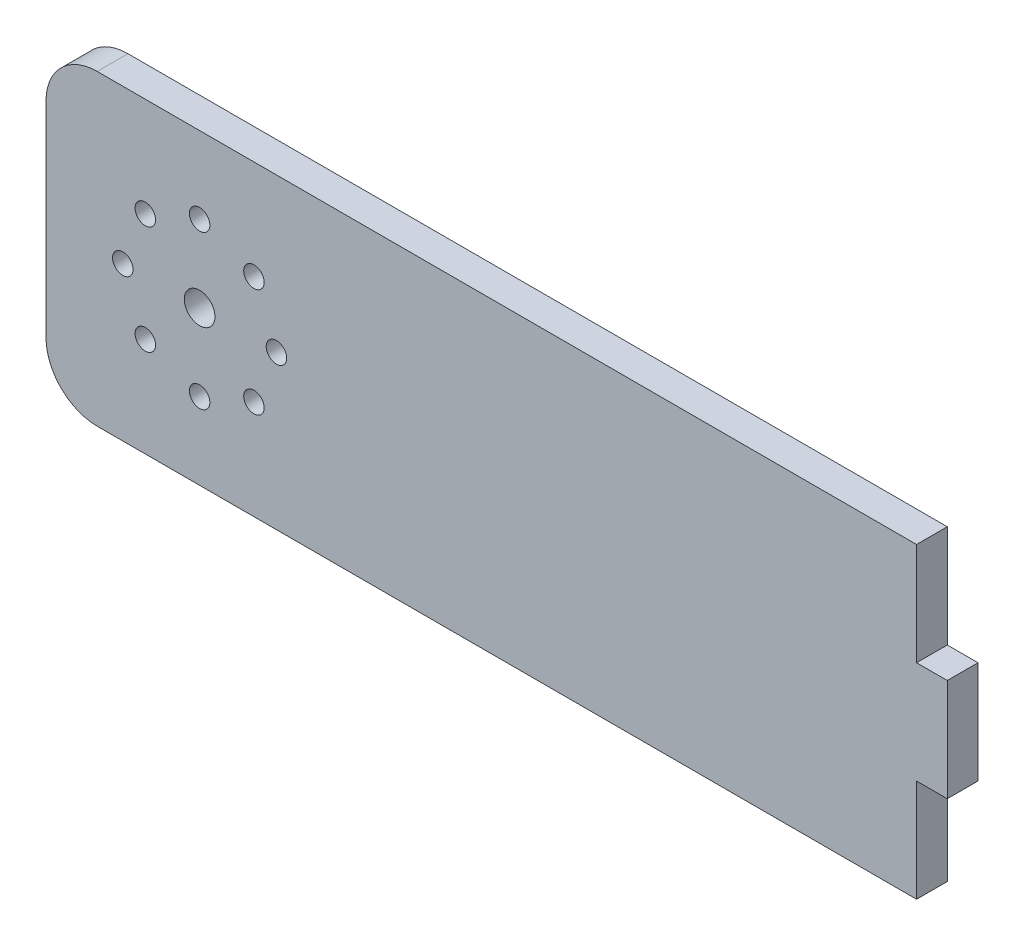
SolidWorks part; units mm, degrees
ref_plane "Front Plane" through (0, 0, 0) normal (0, 0, 1) x (1, 0, 0)
ref_plane "Top Plane" through (0, 0, 0) normal (0, 1, 0) x (1, 0, 0)
ref_plane "Right Plane" through (0, 0, 0) normal (1, 0, 0) x (0, 0, -1)
sketch "Sketch1" plane through (0, 0, 0) normal (0, 0, 1) x (1, 0, 0)
  line L0 (85, 30) -> (85, 20)
  line L1 (0, 0) -> (85, 0)
  line L2 (0, 0) -> (0, 30)
  line L3 (0, 30) -> (85, 30)
  line L4 (85, 0) -> (85, 10)
  line L5 (85, 20) -> (88, 20)
  line L6 (88, 20) -> (88, 10)
  line L7 (88, 10) -> (85, 10)
  line L8 (85, 20) -> (85, 30)
  line L9 (0, 15) -> (15, 15)
  circle A0 centre (15, 15) radius 1.5
  circle A1 centre (7.5, 15) radius 1
  circle A2 centre (9.6967, 20.3033) radius 1
  circle A3 centre (15, 22.5) radius 1
  circle A4 centre (20.3033, 20.3033) radius 1
  circle A5 centre (22.5, 15) radius 1
  circle A6 centre (20.3033, 9.6967) radius 1
  circle A7 centre (15, 7.5) radius 1
  circle A8 centre (9.6967, 9.6967) radius 1
  point P31 (15, 15)
  dimension "D7" = 3
  dimension "D8" = 2
  dimension "D1" = 85
  dimension "D2" = 30
  dimension "D3" = 10
  dimension "D4" = 10
  dimension "D5" = 3
  dimension "D6" = 15
  dimension "D9" = 8
extrude "Boss-Extrude1" add sketch "Sketch1" along normal blind 3
fillet "Fillet1" radius 5 2 edges at (0, 0, 1.5) (0, 30, 1.5)
